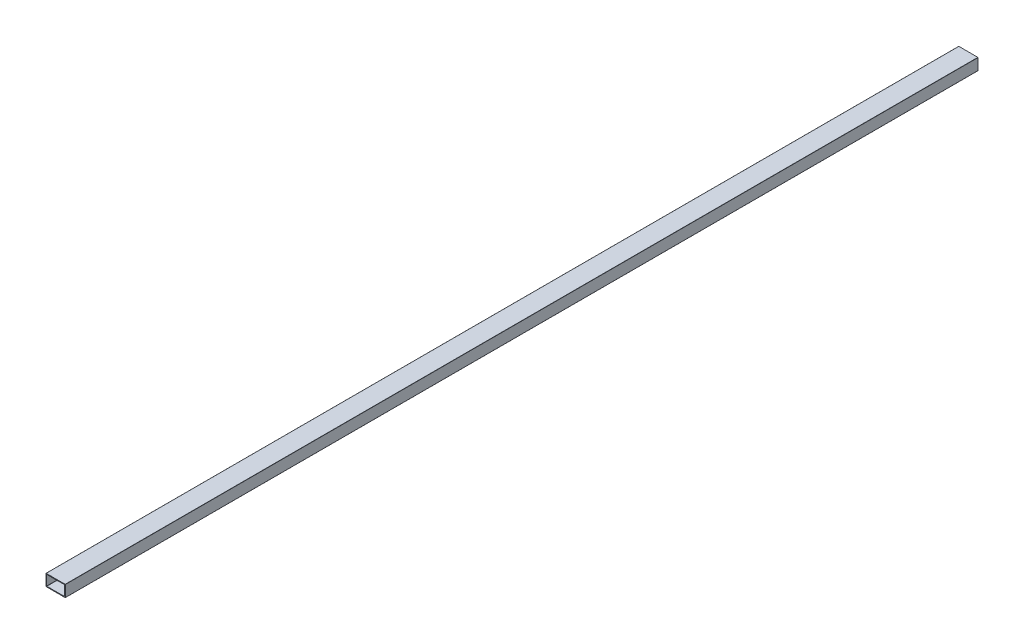
SolidWorks part; units mm, degrees
material "AISI 1035 Acero (SS)"
ref_plane "Alzado" through (0, 0, 0) normal (0, 0, 1) x (1, 0, 0)
ref_plane "Planta" through (0, 0, 0) normal (0, 1, 0) x (1, 0, 0)
ref_plane "Vista lateral" through (0, 0, 0) normal (1, 0, 0) x (0, 0, -1)
sketch "Croquis1" plane through (0, 0, 0) normal (0, 0, 1) x (1, 0, 0)
  line L0 (-58.95, -33.55) -> (-58.95, 33.55)
  line L1 (-63.5, -38.1) -> (63.5, -38.1)
  line L2 (-63.5, -38.1) -> (-63.5, 38.1)
  line L3 (-63.5, 38.1) -> (63.5, 38.1)
  line L4 (63.5, -38.1) -> (63.5, 38.1)
  line L5 (-63.5, -38.1) -> (63.5, 38.1) construction
  line L6 (-63.5, 38.1) -> (63.5, -38.1) construction
  line L7 (-58.95, 33.55) -> (58.95, 33.55)
  line L8 (58.95, -33.55) -> (58.95, 33.55)
  line L9 (-58.95, -33.55) -> (58.95, -33.55)
  point P0 (0, 0)
  dimension "D1" = 76.2
  dimension "D2" = 127
  dimension "D3" = 4.55
extrude "Saliente-Extruir1" add sketch "Croquis1" against normal blind 6000
fillet "Redondeo1" radius 1 8 edges at (-58.95, 33.55, -3000) (58.95, 33.55, -3000) (58.95, -33.55, -3000) (-63.5, -38.1, -3000) (-63.5, 38.1, -3000) (-58.95, -33.55, -3000) (63.5, -38.1, -3000) (63.5, 38.1, -3000)
